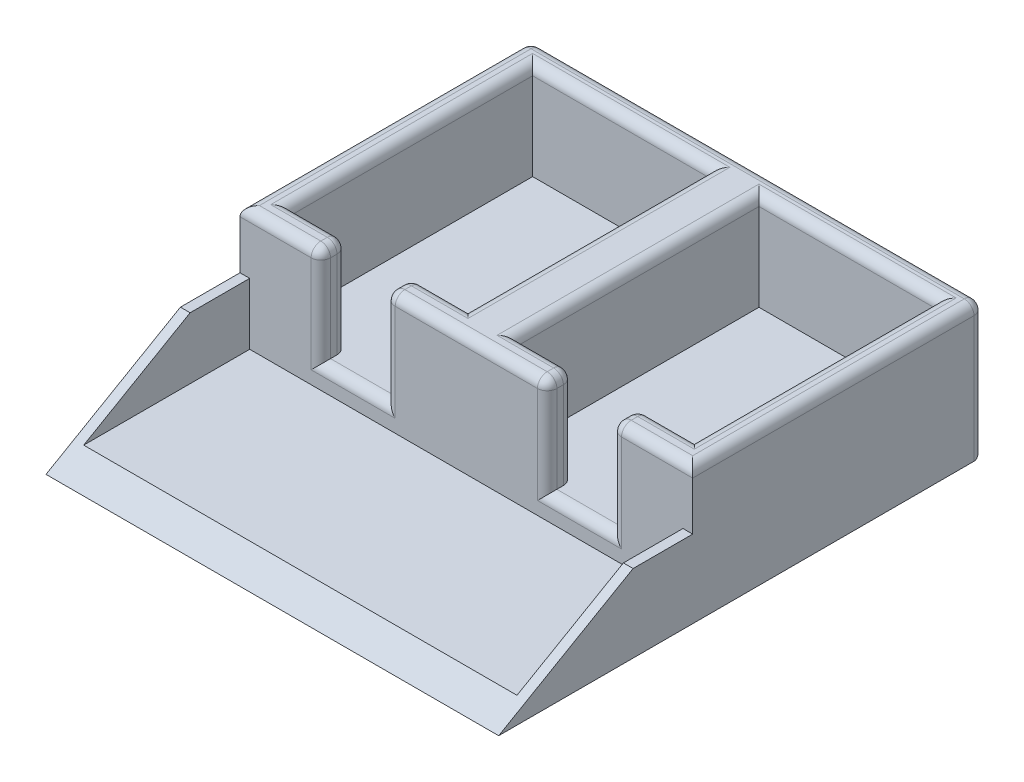
SolidWorks part; units mm, degrees
ref_plane "Front Plane" through (0, 0, 0) normal (0, 0, 1) x (1, 0, 0)
ref_plane "Top Plane" through (0, 0, 0) normal (0, 1, 0) x (1, 0, 0)
ref_plane "Right Plane" through (0, 0, 0) normal (1, 0, 0) x (0, 0, -1)
sketch "Sketch1" plane through (0, 0, 0) normal (0, 1, 0) x (1, 0, 0)
  line L0 (0, 0) -> (140, 0)
  line L1 (-55, 0) -> (55, 0) construction
  line L2 (140, 0) -> (140, 90)
  line L3 (140, 90) -> (0, 90)
  line L4 (0, -55) -> (0, 55) construction
  line L5 (0, 90) -> (0, 0)
  line L6 (70, 90) -> (70, 0) construction
  dimension "D1" = 140
  dimension "D2" = 90
extrude "Boss-Extrude1" add sketch "Sketch1" along normal blind 42
ref_plane "Plane1" through (0, 42, 0) normal (0, 1, 0) x (1, 0, 0)
sketch "Sketch2" plane through (0, 42, 0) normal (0, 1, 0) x (1, 0, 0)
  line L0 (7.5, 8) -> (7.5, 83)
  line L1 (0, 0) -> (140, 0) construction
  line L2 (7.5, 83) -> (62.5, 83)
  line L3 (62.5, 83) -> (62.5, 8)
  line L5 (70, 90) -> (70, 0) construction
  line L6 (140, 90) -> (0, 90) construction
  line L7 (77.5, 8) -> (77.5, 83)
  line L8 (77.5, 83) -> (132.5, 83)
  line L9 (132.5, 83) -> (132.5, 8)
  line L11 (25, 8) -> (25, 0)
  line L12 (7.5, 8) -> (25, 8)
  line L13 (0, 90) -> (0, 0) construction
  line L14 (25, 0) -> (45, 0)
  line L15 (45, 0) -> (45, 8)
  line L17 (95, 8) -> (95, 0)
  line L18 (95, 0) -> (115, 0)
  line L19 (115, 0) -> (115, 8)
  line L21 (45, 8) -> (62.5, 8)
  line L22 (77.5, 8) -> (95, 8)
  line L23 (115, 8) -> (132.5, 8)
  dimension "D1" = 55
  dimension "D2" = 55
  dimension "D3" = 15
  dimension "D4" = 7.5
  dimension "D5" = 75
  dimension "D6" = 75
  dimension "D7" = 20
  dimension "D8" = 17.5
  dimension "D9" = 20
  dimension "D10" = 17.5
extrude "Cut-Extrude1" cut sketch "Sketch2" against normal blind 30
fillet "Fillet2" radius 3 33 edges at (12.5, 42, 0) (0, 42, -45) (140, 21, -90) (140, 42, -45) (127.5, 42, 0) (115, 27, 0) (115, 27, -8) (115, 42, -4) (95, 42, -4) (95, 27, -8) (25, 27, -8) (45, 27, -8) (45, 42, -4) (25, 42, -4) (45, 27, 0) (25, 27, 0) (95, 27, 0) (70, 42, 0) (70, 42, -90) (0, 21, -90) (70, 0, -90) (105, 42, -83) (77.5, 42, -45.5) (132.5, 42, -45.5) (123.75, 42, -8) (86.25, 42, -8) (16.25, 42, -8) (53.75, 42, -8) (62.5, 42, -45.5) (35, 42, -83) (7.5, 42, -45.5) (105, 12, 0) (35, 12, 0)
sketch "Sketch3" plane through (0, 0, 0) normal (0, 1, 0) x (1, 0, 0)
  line L1 (0, 0) -> (140, 0)
  line L2 (0, 0) -> (0, -60)
  line L3 (0, -60) -> (140, -60)
  line L4 (140, 0) -> (140, -60)
  line L5 (140, 0) -> (140, 87) construction
  dimension "D1" = 60
extrude "Boss-Extrude2" add sketch "Sketch3" along normal blind 5
sketch "Sketch4" plane through (0, 5, 0) normal (0, 1, 0) x (1, 0, 0)
  line L0 (0, -60) -> (140, -60) construction
  line L1 (0, 0) -> (3, 0)
  line L2 (0, 0) -> (0, -60)
  line L3 (0, -60) -> (3, -60)
  line L4 (3, 0) -> (3, -60)
  line L6 (140, 0) -> (137, 0)
  line L7 (140, 0) -> (140, -60)
  line L8 (140, -60) -> (137, -60)
  line L9 (137, 0) -> (137, -60)
  dimension "D1" = 3
  dimension "D2" = 3
extrude "Boss-Extrude3" add sketch "Sketch4" along normal blind 19
sketch "Sketch5" plane through (0, 0, 0) normal (-1, 0, 0) x (0, 0, 1)
  line L0 (60, 0) -> (8.0385, 30)
  line L1 (-87, 0) -> (60, 0) construction
  line L2 (8.0385, 30) -> (60, 30)
  line L3 (60, 30) -> (60, 0)
  dimension "D1" = 60
  dimension "D2" = 30
extrude "Cut-Extrude2" cut sketch "Sketch5" against normal through all both and the other way through all
